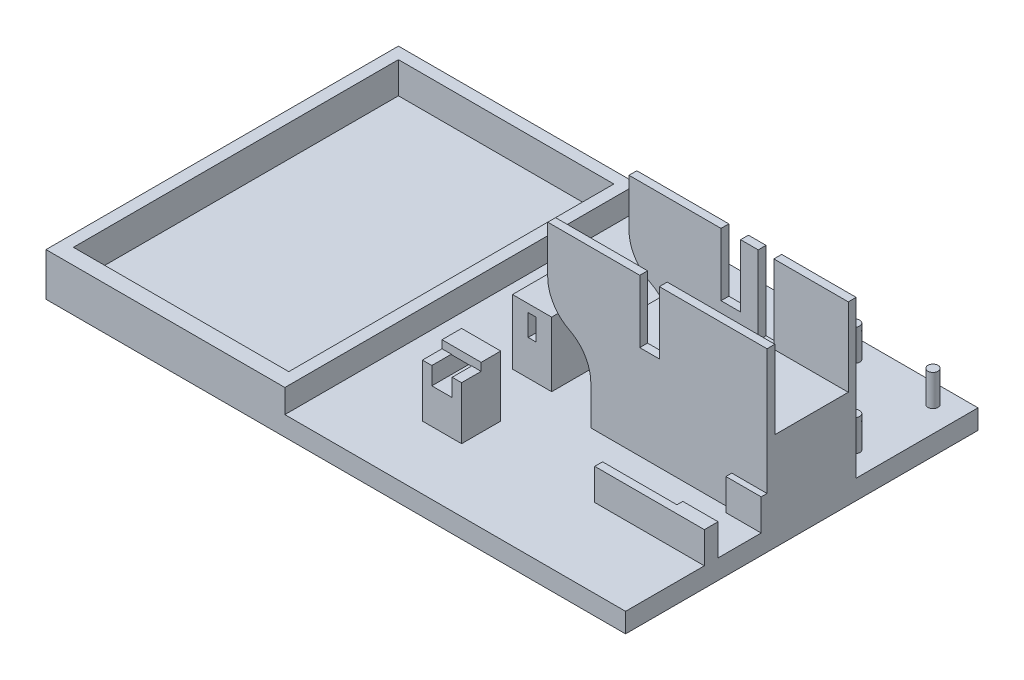
SolidWorks part; units mm, degrees
ref_plane "Front Plane" through (0, 0, 0) normal (0, 0, 1) x (1, 0, 0)
ref_plane "Top Plane" through (0, 0, 0) normal (0, 1, 0) x (1, 0, 0)
ref_plane "Right Plane" through (0, 0, 0) normal (1, 0, 0) x (0, 0, -1)
sketch "Sketch3" plane through (0, 0, 0) normal (0, 1, 0) x (1, 0, 0)
  line L1 (-60, -42.5) -> (60, -42.5)
  line L2 (-60, -42.5) -> (-60, 42.5)
  line L3 (-60, 42.5) -> (60, 42.5)
  line L4 (60, -42.5) -> (60, 42.5)
  line L5 (-60, -42.5) -> (60, 42.5) construction
  line L6 (-60, 42.5) -> (60, -42.5) construction
  point P0 (0, 0)
  dimension "D1" = 120
  dimension "D2" = 85
extrude "Boss-Extrude1" add sketch "Sketch3" along normal blind 5
sketch "Sketch4" plane through (0, 5, 0) normal (0, 1, 0) x (1, 0, 0)
  line L0 (-66.2626, 0) -> (69.7258, 0) construction
  line L1 (60, -42.5) -> (60, 42.5) construction
  line L2 (15, -9.375) -> (60, -9.375)
  line L3 (15, -9.375) -> (15, 9.375)
  line L4 (15, 9.375) -> (60, 9.375)
  line L5 (60, -9.375) -> (60, 9.375)
  line L6 (15, -9.375) -> (60, 9.375) construction
  line L7 (15, 9.375) -> (60, -9.375) construction
  point P3 (37.5, 0)
  dimension "D1" = 18.75
  dimension "D2" = 45
extrude "Boss-Extrude2" add sketch "Sketch4" along normal blind 20
sketch "Sketch6" plane through (0, 5, 0) normal (0, 1, 0) x (1, 0, 0)
  line L0 (60, 9.375) -> (60, 42.5) construction
  line L1 (15, 9.375) -> (60, 9.375)
  line L2 (15, 9.375) -> (15, 11.375)
  line L3 (15, 11.375) -> (60, 11.375)
  line L4 (60, 9.375) -> (60, 11.375)
  line L5 (60, -42.5) -> (60, -9.375) construction
  line L6 (15, -9.375) -> (60, -9.375)
  line L7 (15, -9.375) -> (15, -11.375)
  line L8 (15, -11.375) -> (60, -11.375)
  line L9 (60, -9.375) -> (60, -11.375)
  point P14 (37.5, 11.375)
  dimension "D1" = 2
  dimension "D2" = 2
extrude "Boss-Extrude3" add sketch "Sketch6" along normal blind 40
sketch "Sketch7" plane through (0, 45, 0) normal (0, 1, 0) x (1, 0, 0)
  line L1 (41, 11.375) -> (37, 11.375)
  line L2 (41, 11.375) -> (41, 9.375)
  line L3 (41, 9.375) -> (37, 9.375)
  line L4 (15, 11.375) -> (15, 9.375)
  line L5 (15, 9.375) -> (60, 9.375)
  line L6 (60, 9.375) -> (60, 11.375)
  line L7 (60, 11.375) -> (15, 11.375)
  line L8 (15, 11.375) -> (15, 9.375)
  line L9 (15, 9.375) -> (60, 9.375)
  line L10 (60, 9.375) -> (60, 11.375)
  line L11 (60, 11.375) -> (15, 11.375)
  line L12 (37, 11.375) -> (37, 9.375)
  dimension "D2" = 23
  dimension "D3" = 19
  dimension "D1" = 0
extrude "Cut-Extrude1" cut sketch "Sketch7" against normal up to surface (20 mm away) and the other way through all contours L2 L1 L12 L3 up to face at (37.5, 25, 0)
sketch "Sketch8" plane through (0, 5, 0) normal (0, 1, 0) x (1, 0, 0)
  line L0 (15, -9.375) -> (60, -9.375) construction
  line L1 (-8, 11.625) -> (2, 11.625)
  line L2 (-8, 11.625) -> (-8, -8.375)
  line L3 (-8, -8.375) -> (2, -8.375)
  line L4 (2, 11.625) -> (2, -8.375)
  line L5 (60, -9.375) -> (60, 9.375) construction
  point P6 (-3, -8.375)
  dimension "D1" = 10
  dimension "D2" = 1
  dimension "D3" = 63
  dimension "D4" = 20
extrude "Boss-Extrude4" add sketch "Sketch8" along normal blind 9
sketch "Sketch9" plane through (0, 14, 0) normal (0, 1, 0) x (1, 0, 0)
  line L0 (2, -8.375) -> (2, 11.625) construction
  line L1 (-8, -8.375) -> (2, -8.375)
  line L2 (-8, -8.375) -> (-8, 1.625)
  line L3 (-8, 1.625) -> (-5.25, 1.625)
  line L4 (2, -8.375) -> (2, 1.625)
  line L5 (-5.25, 1.625) -> (-5.25, -6.375)
  line L6 (-0.75, 1.625) -> (-0.75, -6.375)
  line L7 (-5.25, -6.375) -> (-0.75, -6.375)
  line L8 (-0.75, 1.625) -> (2, 1.625)
  dimension "D3" = 2
extrude "Boss-Extrude5" add sketch "Sketch9" along normal blind 5.5
sketch "Sketch10" plane through (0, 0, 8.375) normal (0, 0, 1) x (1, 0, 0)
  line L0 (-8, 19.5) -> (2, 19.5) construction
  line L1 (-4, 19.5) -> (-2, 19.5)
  line L2 (-4, 19.5) -> (-4, 14)
  line L3 (-4, 14) -> (-2, 14)
  line L4 (-2, 19.5) -> (-2, 14)
  line L5 (2, 19.5) -> (2, 5) construction
  dimension "D1" = 5.5
  dimension "D2" = 2
  dimension "D3" = 4
extrude "Cut-Extrude2" cut sketch "Sketch10" against normal through all
sketch "Sketch11" plane through (0, 19.5, 0) normal (0, 1, 0) x (1, 0, 0)
  line L0 (-8, 11.625) -> (-8, -8.375) construction
  line L1 (-8, 1.625) -> (2, 1.625)
  line L2 (-8, 1.625) -> (-8, -8.375)
  line L3 (-8, -8.375) -> (2, -8.375)
  line L4 (2, 1.625) -> (2, -8.375)
extrude "Boss-Extrude6" add sketch "Sketch11" along normal blind 2
sketch "Sketch12" plane through (0, 5, 0) normal (0, 1, 0) x (1, 0, 0)
  line L0 (-8, 11.625) -> (-8, 1.625) construction
  line L1 (-8, -21.375) -> (2, -21.375)
  line L2 (-8, -21.375) -> (-8, -31.375)
  line L3 (-8, -31.375) -> (2, -31.375)
  line L4 (2, -21.375) -> (2, -31.375)
  line L7 (15, -9.375) -> (60, -9.375) construction
  dimension "D1" = 10
  dimension "D2" = 0
  dimension "D3" = 10
  dimension "D4" = 12
extrude "Boss-Extrude7" add sketch "Sketch12" along normal blind 9
sketch "Sketch13" plane through (0, 14, 0) normal (0, 1, 0) x (1, 0, 0)
  line L15 (2, -21.375) -> (-8, -21.375) construction
  line L16 (-5.6, -21.375) -> (-0.4, -21.375)
  line L17 (-5.6, -21.375) -> (-5.6, -31.375)
  line L18 (-5.6, -31.375) -> (-0.4, -31.375)
  line L19 (-0.4, -21.375) -> (-0.4, -31.375)
  line L20 (-8, -21.375) -> (-8, -31.375) construction
  line L23 (-8, -31.375) -> (2, -31.375) construction
  line L24 (-8, -21.375) -> (-5.6, -21.375)
  line L25 (-8, -21.375) -> (-8, -31.375)
  line L26 (-8, -31.375) -> (-5.6, -31.375)
  line L27 (-5.6, -21.375) -> (-5.6, -31.375)
  line L29 (-0.4, -21.375) -> (2, -21.375)
  line L30 (-0.4, -21.375) -> (-0.4, -31.375)
  line L31 (-0.4, -31.375) -> (2, -31.375)
  line L32 (2, -21.375) -> (2, -31.375)
  dimension "D1" = 5.2
  dimension "D2" = 2.4
extrude "Boss-Extrude8" add sketch "Sketch13" along normal blind 4.5 contours L25 L24 L27 L26 | L30 L29 L32 L31
sketch "Sketch14" plane through (0, 18.5, 0) normal (0, 1, 0) x (1, 0, 0)
  line L0 (2, -21.375) -> (2, -31.375) construction
  line L1 (-8, -21.375) -> (2, -21.375)
  line L2 (-8, -21.375) -> (-8, -26.375)
  line L3 (-8, -26.375) -> (2, -26.375)
  line L4 (2, -21.375) -> (2, -26.375)
extrude "Boss-Extrude9" add sketch "Sketch14" along normal blind 2
sketch "Sketch15" plane through (0, 5, 0) normal (0, 1, 0) x (1, 0, 0)
  line L0 (60, 42.5) -> (-60, 42.5) construction
  line L1 (30, 39.5) -> (57, 39.5)
  line L2 (30, 39.5) -> (30, 13.5)
  line L3 (30, 13.5) -> (57, 13.5)
  line L4 (57, 39.5) -> (57, 13.5)
  line L5 (60, 11.375) -> (60, 42.5) construction
  circle A0 centre (33.5, 37.5) radius 1.3
  circle A2 centre (53.5, 37.5) radius 1.3
  circle A3 centre (53.5, 17.5) radius 1.3
  circle A4 centre (33.5, 17.5) radius 1.3
  dimension "D5" = 2.6
  dimension "D6" = 2.6
  dimension "D7" = 2.6
  dimension "D8" = 2.6
  dimension "D16" = 6.5
  dimension "D1" = 27
  dimension "D2" = 26
  dimension "D3" = 3
  dimension "D4" = 3
  dimension "D9" = 20
  dimension "D10" = 20
  dimension "D11" = 20
  dimension "D12" = 20
  dimension "D13" = 3.5
  dimension "D14" = 2
  dimension "D15" = 20
extrude "Boss-Extrude10" add sketch "Sketch15" along normal blind 8 contours A4 | A3 | A0 | A2
sketch "Sketch16" plane through (0, 5, 0) normal (0, 1, 0) x (1, 0, 0)
  line L0 (60, -42.5) -> (60, -11.375) construction
  line L4 (60, -11.5) -> (60, -12.875)
  line L6 (15, -11.375) -> (60, -11.375) construction
  line L12 (51, -11.375) -> (60, -11.375)
  line L13 (51, -11.375) -> (51, -12.875)
  line L14 (51, -12.875) -> (60, -12.875)
  line L15 (60, -11.375) -> (60, -12.875)
  line L21 (32, -25.375) -> (60, -25.375)
  line L22 (32, -25.375) -> (32, -27.375)
  line L23 (32, -27.375) -> (60, -27.375)
  line L24 (60, -25.375) -> (60, -27.375)
  line L25 (51, -25.375) -> (60, -25.375)
  line L26 (51, -25.375) -> (51, -23.875)
  line L27 (51, -23.875) -> (60, -23.875)
  line L28 (60, -25.375) -> (60, -23.875)
  dimension "D1" = 2
  dimension "D2" = 28
  dimension "D3" = 0
  dimension "D4" = 9
  dimension "D5" = 14
  dimension "D6" = 1.5
  dimension "D7" = 9
  dimension "D8" = 1.5
extrude "Boss-Extrude11" add sketch "Sketch16" along normal blind 8 contours L22 L21 L24 L23 | L26 L25 L28 L27 | L13 L12 L15 L14
sketch "Sketch18" plane through (0, 0, 42.5) normal (0, 0, 1) x (1, 0, 0)
  line L4 (-60, 0) -> (60, 0)
  line L5 (60, 0) -> (60, 5)
  line L6 (60, 5) -> (-60, 5)
  line L7 (-60, 5) -> (-60, 0)
  line L8 (-60, 0) -> (60, 0)
  line L9 (60, 0) -> (60, 5)
  line L10 (60, 5) -> (-60, 5)
  line L11 (-60, 5) -> (-60, 0)
  dimension "D1" = 0
extrude "Boss-Extrude12" add sketch "Sketch18" along normal blind 5
sketch "Sketch19" plane through (-60, 0, 0) normal (-1, 0, 0) x (0, 0, 1)
  line L4 (-42.5, 0) -> (47.5, 0)
  line L5 (47.5, 0) -> (47.5, 5)
  line L6 (47.5, 5) -> (-42.5, 5)
  line L7 (-42.5, 5) -> (-42.5, 0)
  line L8 (-42.5, 0) -> (47.5, 0)
  line L9 (47.5, 0) -> (47.5, 5)
  line L10 (47.5, 5) -> (-42.5, 5)
  line L11 (-42.5, 5) -> (-42.5, 0)
  dimension "D1" = 0
extrude "Boss-Extrude13" add sketch "Sketch19" along normal blind 30
sketch "Sketch17" plane through (0, 5, 0) normal (0, 1, 0) x (1, 0, 0)
  line L0 (60, -47.5) -> (60, -27.375) construction
  line L1 (-85, 39.5) -> (-30, 39.5)
  line L2 (-85, 39.5) -> (-85, -43.5)
  line L3 (-85, -43.5) -> (-30, -43.5)
  line L4 (-30, 39.5) -> (-30, -43.5)
  line L7 (60, 42.5) -> (-90, 42.5) construction
  dimension "D1" = 83
  dimension "D2" = 55
  dimension "D3" = 90
  dimension "D4" = 3
extrude "Cut-Extrude3" cut sketch "Sketch17" against normal blind 2
sketch "Sketch20" plane through (0, 5, 0) normal (0, 1, 0) x (1, 0, 0)
  line L1 (-88, 42.5) -> (-27, 42.5)
  line L2 (-88, 42.5) -> (-88, -47.5)
  line L3 (-88, -47.5) -> (-27, -47.5)
  line L4 (-85, 39.5) -> (-85, -43.5)
  line L5 (-85, -43.5) -> (-30, -43.5)
  line L6 (-30, -43.5) -> (-30, 39.5)
  line L7 (-30, 39.5) -> (-85, 39.5)
  line L8 (-85, 39.5) -> (-85, -43.5)
  line L9 (-85, -43.5) -> (-30, -43.5)
  line L10 (-30, -43.5) -> (-30, 39.5)
  line L11 (-30, 39.5) -> (-85, 39.5)
  line L12 (-27, 42.5) -> (-27, -47.5)
  line L13 (60, -47.5) -> (-90, -47.5) construction
  dimension "D2" = 3
  dimension "D3" = 3
  dimension "D4" = 3
  dimension "D5" = 0
  dimension "D1" = 0
extrude "Boss-Extrude14" add sketch "Sketch20" along normal blind 6
sketch "Sketch21" plane through (0, 5, 0) normal (0, 1, 0) x (1, 0, 0)
  line L4 (-88, -47.5) -> (-88, 42.5)
  line L5 (-88, 42.5) -> (-90, 42.5)
  line L6 (-90, 42.5) -> (-90, -47.5)
  line L7 (-90, -47.5) -> (-88, -47.5)
  line L8 (-88, -47.5) -> (-88, 42.5)
  line L9 (-88, 42.5) -> (-90, 42.5)
  line L10 (-90, 42.5) -> (-90, -47.5)
  line L11 (-90, -47.5) -> (-88, -47.5)
  dimension "D1" = 0
extrude "Cut-Extrude4" cut sketch "Sketch21" against normal through all
sketch "Sketch22" plane through (0, 45, 0) normal (0, 1, 0) x (1, 0, 0)
  line L0 (60, 11.375) -> (15, 11.375) construction
  line L1 (27.5, 11.375) -> (32.5, 11.375)
  line L2 (27.5, 11.375) -> (27.5, -11.375)
  line L3 (27.5, -11.375) -> (32.5, -11.375)
  line L4 (32.5, 11.375) -> (32.5, -11.375)
  line L5 (15, -11.375) -> (60, -11.375) construction
  line L6 (15, -9.375) -> (15, -11.375) construction
  point P8 (30, -11.375)
  dimension "D1" = 15
  dimension "D2" = 5
extrude "Cut-Extrude5" cut sketch "Sketch22" against normal blind 16
sketch "Sketch23" plane through (15, 0, 0) normal (-1, 0, 0) x (0, 0, 1)
  line L0 (11.375, 45) -> (11.375, 5) construction
  line L1 (-11.375, 45) -> (-9.375, 45)
  line L2 (-11.375, 45) -> (-11.375, 25)
  line L3 (-11.375, 25) -> (-9.375, 25)
  line L4 (-9.375, 45) -> (-9.375, 25)
  line L5 (9.375, 45) -> (11.375, 45)
  line L6 (9.375, 45) -> (9.375, 25)
  line L7 (9.375, 25) -> (11.375, 25)
  line L8 (11.375, 45) -> (11.375, 25)
extrude "Boss-Extrude15" add sketch "Sketch23" along normal blind 11
fillet "Fillet1" radius 10 2 edges at (15, 25, 10.375) (15, 25, -10.375)
fillet "Fillet2" radius 10 2 edges at (4, 25, -10.375) (4, 25, 10.375)
sketch "Sketch24" plane through (0, 0, -1.625) normal (0, 0, -1) x (-1, 0, 0)
  line L0 (5.25, 14) -> (8, 14) construction
  line L1 (5.25, 19.5) -> (5.35, 19.5)
  line L2 (5.25, 19.5) -> (5.25, 14)
  line L3 (5.25, 14) -> (5.35, 14)
  line L4 (5.35, 19.5) -> (5.35, 14)
  line L5 (-2, 14) -> (0.75, 14) construction
  line L6 (0.75, 19.5) -> (0.65, 19.5)
  line L7 (0.75, 19.5) -> (0.75, 14)
  line L8 (0.75, 14) -> (0.65, 14)
  line L9 (0.65, 19.5) -> (0.65, 14)
  line L11 (0.65, 19.5) -> (5.35, 19.5)
  line L12 (0.65, 19.5) -> (0.65, 19.6)
  line L13 (0.65, 19.6) -> (5.35, 19.6)
  line L14 (5.35, 19.5) -> (5.35, 19.6)
  dimension "D1" = 0.1
  dimension "D2" = 0.1
  dimension "D3" = 0.1
extrude "Cut-Extrude6" cut sketch "Sketch24" against normal up to surface (8 mm away) contours L2 L1 L4 L3 | L12 L11 L14 L13 | L7 L6 L9 L8 up to face at (-4.625, 16.75, 6.375)
sketch "Sketch25" plane through (0, 0, 21.375) normal (0, 0, -1) x (-1, 0, 0)
  line L0 (5.6, 18.5) -> (5.6, 14) construction
  line L1 (0.4, 18.5) -> (5.6, 18.5)
  line L2 (0.4, 18.5) -> (0.4, 18.4)
  line L3 (0.4, 18.4) -> (5.6, 18.4)
  line L4 (5.6, 18.5) -> (5.6, 18.4)
  dimension "D1" = 0.1
extrude "Boss-Extrude16" add sketch "Sketch25" against normal up to surface (5 mm away) up to face at (-3, 19.1667, 26.375)
